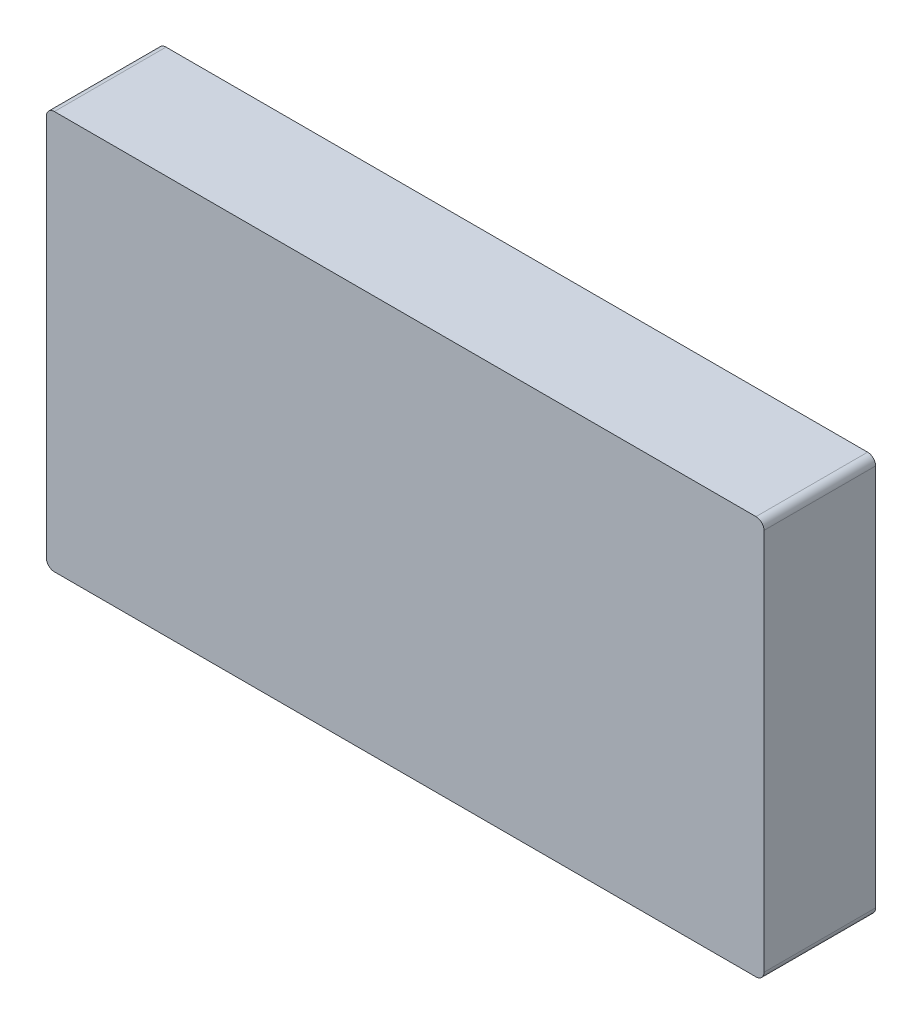
SolidWorks part; units mm, degrees
material "硅"
ref_plane "前视基准面" through (0, 0, 0) normal (0, 0, 1) x (1, 0, 0)
ref_plane "上视基准面" through (0, 0, 0) normal (0, 1, 0) x (1, 0, 0)
ref_plane "右视基准面" through (0, 0, 0) normal (1, 0, 0) x (0, 0, -1)
sketch "草图1" plane through (0, 0, 0) normal (0, 0, 1) x (1, 0, 0)
  line L1 (-3.6466, 3.4009) -> (0.8534, 3.4009)
  line L2 (-3.6466, 3.4009) -> (-3.6466, 0.9009)
  line L3 (-3.6466, 0.9009) -> (0.8534, 0.9009)
  line L4 (0.8534, 3.4009) -> (0.8534, 0.9009)
  dimension "D1" = 4.5
  dimension "D2" = 2.5
extrude "凸台-拉伸1" add sketch "草图1" along normal blind 0.7
fillet "圆角1" radius 0.05 4 edges at (-3.6466, 3.4009, 0.35) (0.8534, 3.4009, 0.35) (0.8534, 0.9009, 0.35) (-3.6466, 0.9009, 0.35)
